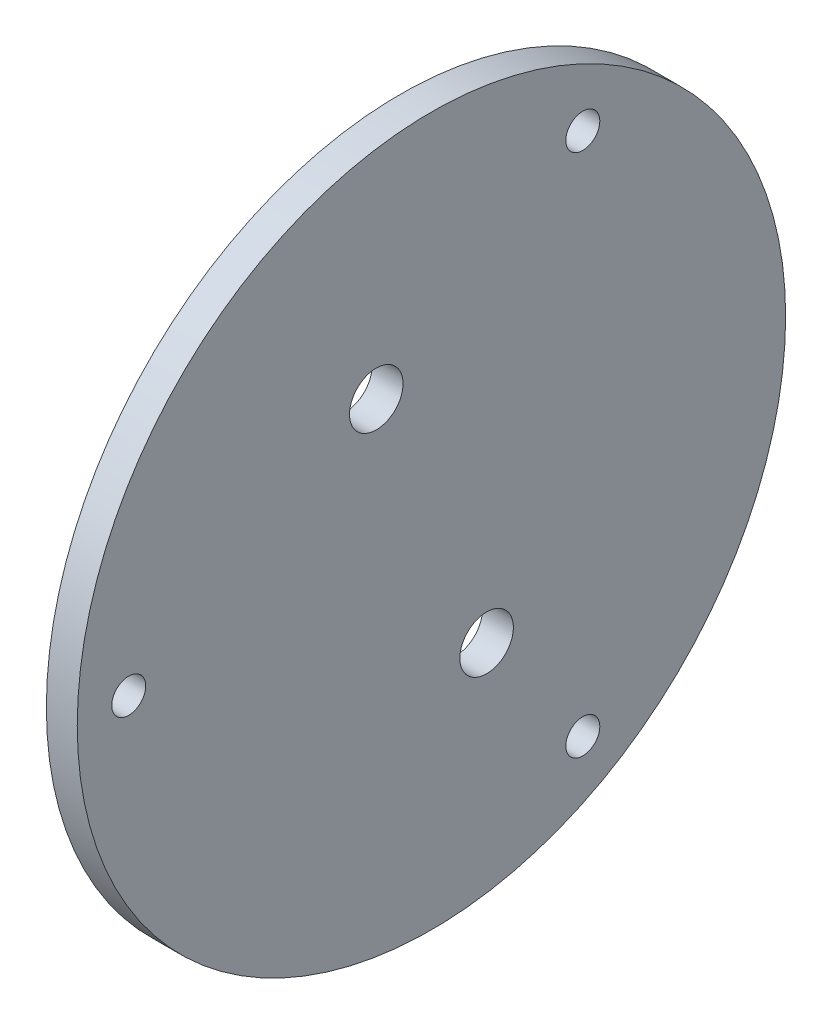
SolidWorks part; units mm, degrees
ref_plane "Front Plane" through (0, 0, 0) normal (0, 0, 1) x (1, 0, 0)
ref_plane "Top Plane" through (0, 0, 0) normal (0, 1, 0) x (1, 0, 0)
ref_plane "Right Plane" through (0, 0, 0) normal (1, 0, 0) x (0, 0, -1)
sketch "Axial profile (mm)" plane through (0, 0, 0) normal (0, 0, 1) x (1, 0, 0)
  line L0 (-110, 0) -> (75, 0) construction
  line L1 (156.7, 0) -> (159.7, 0)
  line L2 (159.7, 0) -> (159.7, 34.4)
  line L3 (159.7, 34.4) -> (156.7, 34.4)
  line L4 (156.7, 34.4) -> (156.7, 0)
revolve "Full revolution" add sketch "Axial profile (mm)" angle 360 about L0
sketch "Sketch2" plane through (0, 0, 0) normal (1, 0, 0) x (0, 0, -1)
  circle A0 centre (-5.3576, 12.9343) radius 2.6
  circle A1 centre (5.3576, -12.9343) radius 2.6
  circle A2 centre (-29.4, 0) radius 1.65
  circle A3 centre (14.7, -25.4611) radius 1.65
  circle A4 centre (14.7, 25.4611) radius 1.65
extrude "Axial holes" cut sketch "Sketch2" against normal through all and the other way through all
